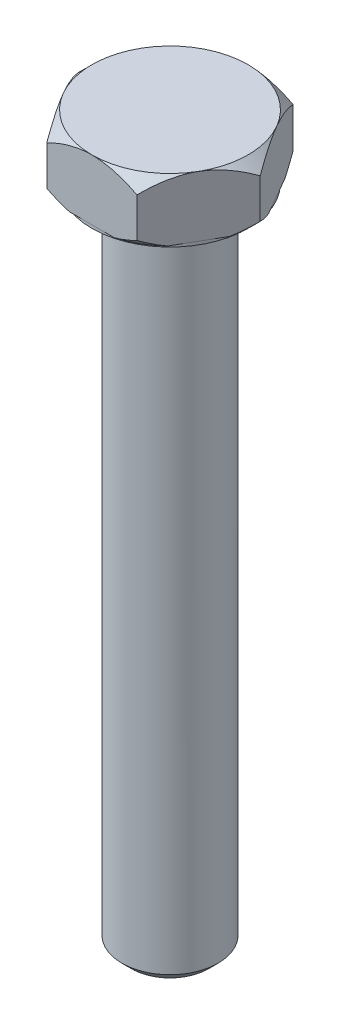
SolidWorks part; units mm, degrees
material "Cast Stainless Steel"
ref_plane "Front Plane" through (0, 0, 0) normal (0, 0, 1) x (1, 0, 0)
ref_plane "Top Plane" through (0, 0, 0) normal (0, 1, 0) x (1, 0, 0)
ref_plane "Right Plane" through (0, 0, 0) normal (1, 0, 0) x (0, 0, -1)
sketch "Sketch1" plane through (0, 0, 0) normal (0, 1, 0) x (1, 0, 0)
  line L0 (0, 0) -> (7.5056, 0) construction
  line L1 (7.5056, 0) -> (3.7528, 6.5)
  line L2 (3.7528, 6.5) -> (-3.7528, 6.5)
  line L3 (-3.7528, 6.5) -> (-7.5056, 0)
  line L4 (-7.5056, 0) -> (-3.7528, -6.5)
  line L5 (-3.7528, -6.5) -> (3.7528, -6.5)
  line L6 (3.7528, -6.5) -> (7.5056, 0)
  circle A0 centre (0, 0) radius 6.5 construction
  dimension "D1" = 13
extrude "Boss-Extrude1" add sketch "Sketch1" against normal blind 5.3
sketch "Sketch4" plane through (0, 0, 0) normal (1, 0, 0) x (0, 0, -1)
  line L0 (-6.5, 0) -> (-8.15, 0)
  line L1 (-8.15, 0) -> (-8.15, -1.65)
  line L2 (-8.15, -1.65) -> (-6.5, 0)
  line L3 (-6.5, -2.65) -> (6.5, -2.65) construction
  line L4 (-8.15, -3.65) -> (-6.5, -5.3)
  line L5 (-8.15, -5.3) -> (-8.15, -3.65)
  line L6 (-6.5, -5.3) -> (-8.15, -5.3)
  line L7 (0, 0) -> (0, -2.65) construction
  dimension "D1" = 45
  dimension "D2" = 2.65
  dimension "D3" = 1.65
  dimension "D4" = 13
revolve "Cut-Revolve1" cut sketch "Sketch4" angle 360 about L7
sketch "Sketch2" plane through (0, -5.3, 0) normal (0, -1, 0) x (1, 0, 0)
  circle A0 centre (0, 0) radius 6.5
  dimension "D1" = 13
extrude "Cut-Extrude1" cut sketch "Sketch2" against normal blind 0.265 flip side to cut
sketch "Sketch3" plane through (0, -5.3, 0) normal (0, -1, 0) x (1, 0, 0)
  circle A0 centre (0, 0) radius 4
  dimension "D1" = 8
extrude "Boss-Extrude2" add sketch "Sketch3" along normal blind 55
chamfer "Chamfer1" distance 0.8 angle 45 1 edges at (0, -60.3, -4)
equation "\"k\"= 5.3"
equation "\"e\"= 14.38"
equation "\"S\"= 13"
equation "\"L\"=55"
equation "\"D1@Sketch1\"=\"S\""
equation "\"D1@Boss-Extrude1\"=\"k\""
equation "\"D1@Sketch2\"=\"S\""
equation "\"D1@Cut-Extrude1\"=\"k\"/20"
equation "\"d\"= 8"
equation "\"D1@Sketch3\"=\"d\""
equation "\"D1@Boss-Extrude2\"=\"L\""
equation "\"D2@Sketch4\"=\"k\"/2"
equation "\"D3@Sketch4\"=\"D2@Sketch4\"-1"
equation "\"D4@Sketch4\"=\"S\""
equation "\"D1@Chamfer1\"=\"d\"/10"
